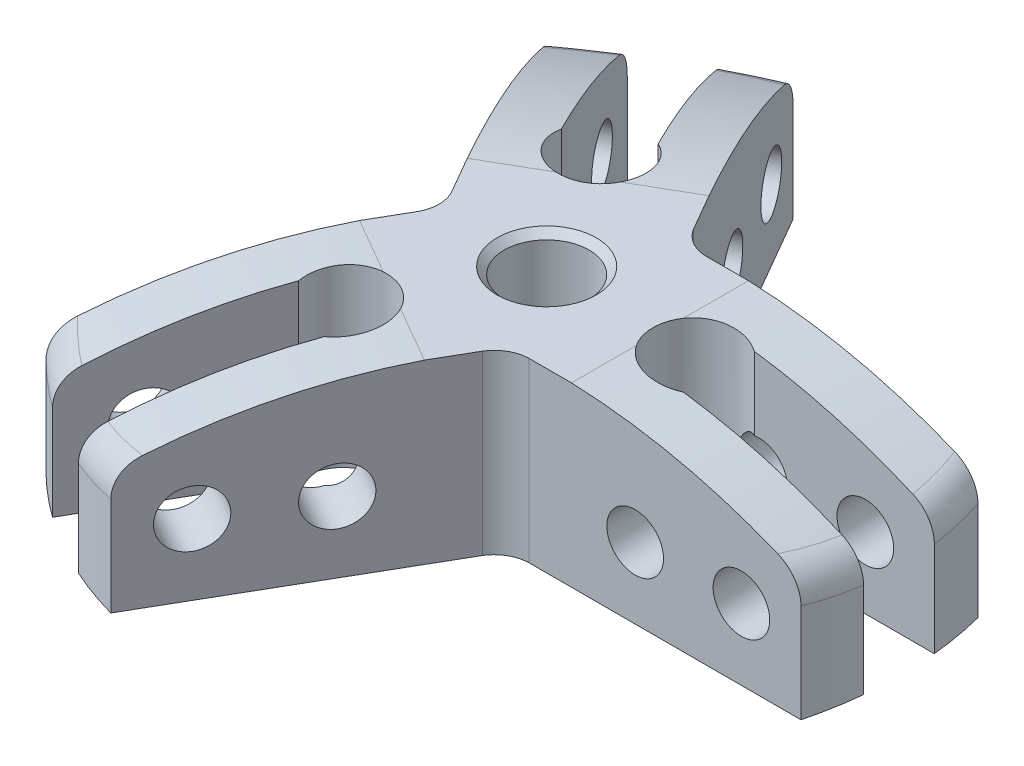
SolidWorks part; units mm, degrees
ref_plane "Front Plane" through (0, 0, 0) normal (0, 0, 1) x (1, 0, 0)
ref_plane "Top Plane" through (0, 0, 0) normal (0, 1, 0) x (1, 0, 0)
ref_plane "Right Plane" through (0, 0, 0) normal (1, 0, 0) x (0, 0, -1)
sketch "Sketch1" plane through (0, 0, 0) normal (0, 1, 0) x (1, 0, 0)
  circle A0 centre (0, 0) radius 50 construction
  circle A1 centre (0, 0) radius 6
  circle A2 centre (0, 0) radius 16
  dimension "D1" = 100
  dimension "D2" = 32
  dimension "D3" = 12
extrude "Boss-Extrude1" add sketch "Sketch1" along normal blind 25
sketch "Sketch2" plane through (0, 0, 0) normal (0, 0, 1) x (1, 0, 0)
  line L0 (0, 0) -> (50, 0)
  line L1 (50, 0) -> (50, 16.4878)
  line L2 (0, 0) -> (0, 25)
  line L3 (6, 25) -> (-6, 25) construction
  line L4 (0, 25) -> (16, 25)
  arc A1 (50, 16.4878) -> (16, 25) centre (12.8002, -59.9398) ccw
  circle A2 centre (40, 10) radius 4
  circle A3 centre (25, 10) radius 4
  dimension "D1" = 85
  dimension "D2" = 50
  dimension "D4" = 8
  dimension "D5" = 10
  dimension "D6" = 40
  dimension "D7" = 25
extrude "Boss-Extrude2" add sketch "Sketch2" along normal mid plane 25
sketch "Sketch4" plane through (0, 25, 0) normal (0, 1, 0) x (1, 0, 0)
  line L0 (50, 0) -> (0, 0) construction
  line L2 (47.2663, 16.3063) -> (75.2307, 16.3063)
  line L3 (75.2307, 16.3063) -> (75.2307, -14.4532)
  line L4 (75.2307, -14.4532) -> (47.8655, -14.4532)
  line L5 (49.7494, 5) -> (24.3166, 5)
  line L8 (24.3166, -5) -> (49.7494, -5)
  arc A0 (47.8655, -14.4532) -> (49.7494, -5) centre (0, 0) ccw
  circle A1 centre (0, 0) radius 6
  arc A2 (24.3166, 5) -> (24.3166, -5) centre (21, 0) ccw
  arc A3 (49.7494, 5) -> (47.2663, 16.3063) centre (0, 0) ccw
  dimension "D2" = 12
  dimension "D3" = 29
extrude "Cut-Extrude2" cut sketch "Sketch4" against normal through all
fillet "Fillet1" radius 5 2 edges
pattern_circular "CirPattern14" count 3 over 360 of "Boss-Extrude2", "Cut-Extrude2", "Fillet1"
sketch "Sketch5" plane through (0, 25, 0) normal (0, 1, 0) x (1, 0, 0)
  line L0 (16, 12.5) -> (9.9875, 12.5) construction
  arc A0 (5.8316, 14.8994) -> (9.9875, 12.5) centre (10.1029, 17.4987) ccw
  arc A1 (9.9875, 12.5) -> (5.8316, 14.8994) centre (0, 0) ccw construction
  dimension "D1" = 5
extrude "Cut-Extrude3" cut sketch "Sketch5" against normal through all and the other way through all
pattern_circular "CirPattern18" count 3 over 360 of "Cut-Extrude3"
chamfer "Chamfer1" distance 1 angle 45 1 edges at (0, 25, 6)
